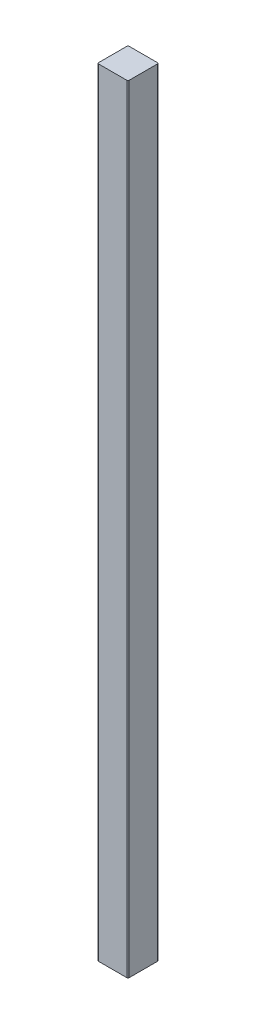
SolidWorks part; units mm, degrees
material "Pine"
ref_plane "Front Plane" through (0, 0, 0) normal (0, 0, 1) x (1, 0, 0)
ref_plane "Top Plane" through (0, 0, 0) normal (0, 1, 0) x (1, 0, 0)
ref_plane "Right Plane" through (0, 0, 0) normal (1, 0, 0) x (0, 0, -1)
sketch "Sketch1" plane through (0, 0, 0) normal (0, 1, 0) x (1, 0, 0)
  line L1 (-44.45, -44.45) -> (44.45, -44.45)
  line L2 (-44.45, -44.45) -> (-44.45, 44.45)
  line L3 (-44.45, 44.45) -> (44.45, 44.45)
  line L4 (44.45, -44.45) -> (44.45, 44.45)
  line L5 (-44.45, -44.45) -> (44.45, 44.45) construction
  line L6 (-44.45, 44.45) -> (44.45, -44.45) construction
  point P0 (0, 0)
  dimension "D1" = 88.9
extrude "Boss-Extrude1" add sketch "Sketch1" along normal blind 2260.6
fillet "Fillet1" radius 3.175 4 edges at (-44.45, 1130.3, -44.45) (44.45, 1130.3, -44.45) (-44.45, 1130.3, 44.45) (44.45, 1130.3, 44.45)
